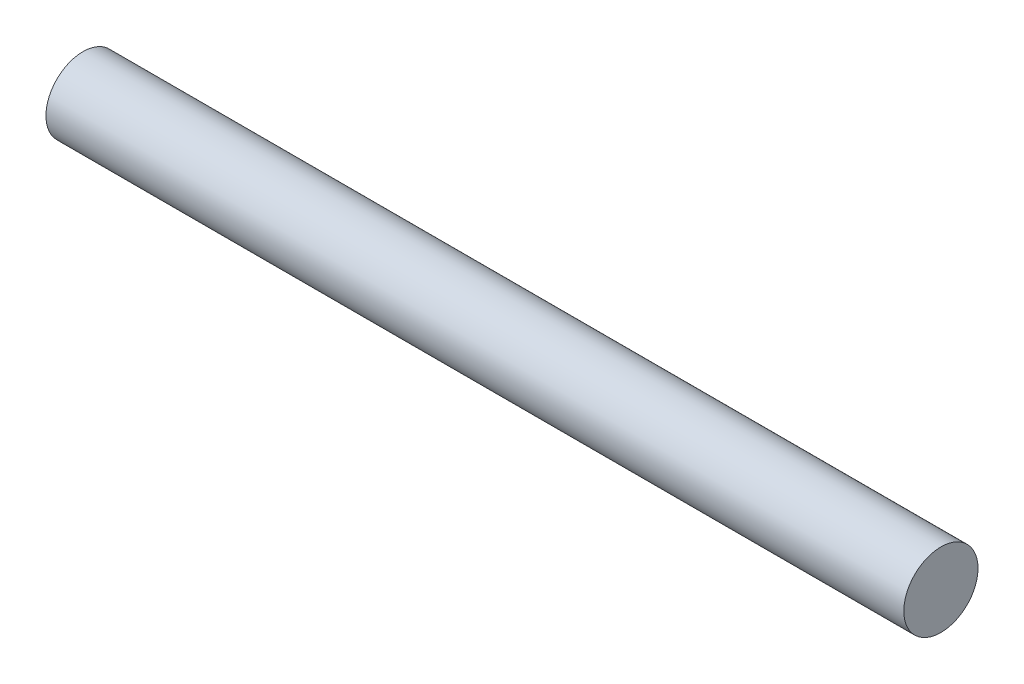
SolidWorks part; units mm, degrees
ref_plane "前视基准面" through (0, 0, 0) normal (0, 0, 1) x (1, 0, 0)
ref_plane "上视基准面" through (0, 0, 0) normal (0, 1, 0) x (1, 0, 0)
ref_plane "右视基准面" through (0, 0, 0) normal (1, 0, 0) x (0, 0, -1)
sketch "草图1" plane through (0, 0, 0) normal (1, 0, 0) x (0, 0, -1)
  circle A0 centre (0, 0) radius 1.6
  dimension "D1" = 3.2
extrude "凸台-拉伸1" add sketch "草图1" along normal blind 37
